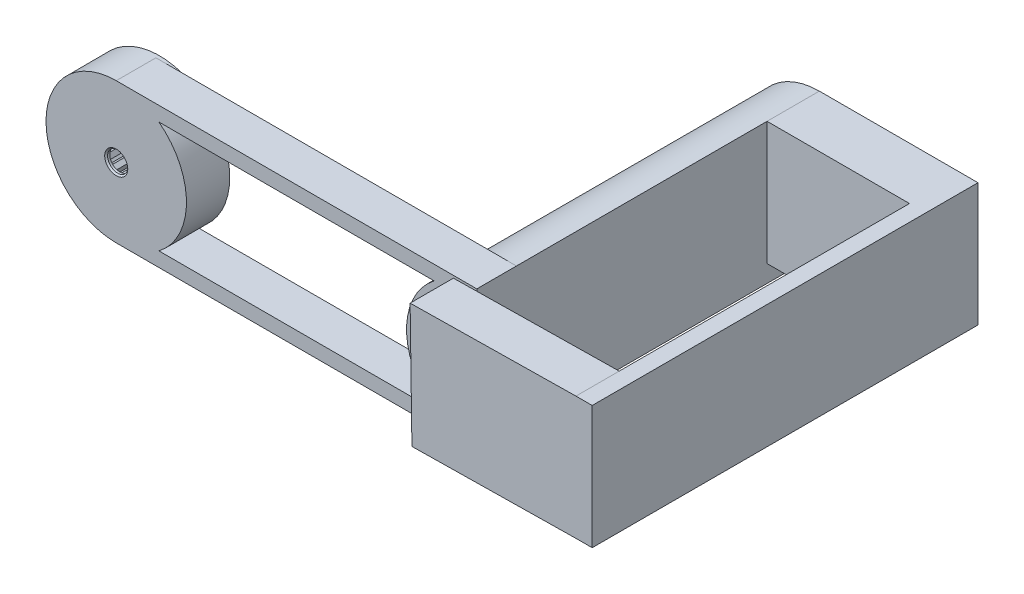
SolidWorks part; units mm, degrees
ref_plane "Plan de face" through (0, 0, 0) normal (0, 0, 1) x (1, 0, 0)
ref_plane "Plan de dessus" through (0, 0, 0) normal (0, 1, 0) x (1, 0, 0)
ref_plane "Plan de droite" through (0, 0, 0) normal (1, 0, 0) x (0, 0, -1)
sketch "Esquisse1" plane through (0, 0, 0) normal (0, 0, 1) x (1, 0, 0)
  line L108 (-5.7517, -9.8772) -> (-6.8338, -9.7825)
  line L109 (-6.8338, -9.7825) -> (-6.9494, -9.1264)
  line L110 (-6.9494, -9.1264) -> (-5.9535, -8.662)
  line L111 (-6.0657, -8.3442) -> (-7.1383, -8.6316)
  line L112 (-7.1383, -8.6316) -> (-7.4714, -8.0546)
  line L113 (-7.4714, -8.0546) -> (-6.6788, -7.262)
  line L114 (-6.8912, -7.0053) -> (-7.818, -7.6542)
  line L115 (-7.818, -7.6542) -> (-8.3284, -7.226)
  line L116 (-8.3284, -7.226) -> (-7.8476, -6.1949)
  line L117 (-8.1333, -6.0289) -> (-8.7911, -6.9683)
  line L118 (-8.7911, -6.9683) -> (-9.4172, -6.7405)
  line L119 (-9.4172, -6.7405) -> (-9.3172, -5.5977)
  line L120 (-9.6413, -5.5414) -> (-9.9401, -6.6566)
  line L121 (-9.9401, -6.6566) -> (-10.6064, -6.6566)
  line L122 (-10.6064, -6.6566) -> (-10.9035, -5.5477)
  line L123 (-11.227, -5.6073) -> (-11.1264, -6.7566)
  line L124 (-11.1264, -6.7566) -> (-11.7525, -6.9845)
  line L125 (-11.7525, -6.9845) -> (-12.4065, -6.0504)
  line L126 (-12.6906, -6.2193) -> (-12.207, -7.2564)
  line L127 (-12.207, -7.2564) -> (-12.7173, -7.6846)
  line L128 (-12.7173, -7.6846) -> (-13.6389, -7.0393)
  line L129 (-13.8487, -7.2983) -> (-13.0514, -8.0955)
  line L130 (-13.0514, -8.0955) -> (-13.3846, -8.6725)
  line L131 (-13.3846, -8.6725) -> (-14.4509, -8.3868)
  line L132 (-14.5599, -8.7057) -> (-13.558, -9.1729)
  line L133 (-13.558, -9.1729) -> (-13.6737, -9.8291)
  line L134 (-13.6737, -9.8291) -> (-14.7493, -9.9232)
  line L135 (-14.7422, -10.2644) -> (-13.6655, -10.3586)
  line L136 (-13.6655, -10.3586) -> (-13.5498, -11.0147)
  line L137 (-13.5498, -11.0147) -> (-14.5063, -11.4608)
  line L138 (-14.3817, -11.783) -> (-13.3609, -11.5095)
  line L139 (-13.3609, -11.5095) -> (-13.0278, -12.0865)
  line L140 (-13.0278, -12.0865) -> (-13.7588, -12.8175)
  line L141 (-13.5298, -13.0811) -> (-12.6812, -12.4869)
  line L142 (-12.6812, -12.4869) -> (-12.1708, -12.9151)
  line L143 (-12.1708, -12.9151) -> (-12.6007, -13.8372)
  line L144 (-12.2937, -14.0091) -> (-11.7081, -13.1728)
  line L145 (-11.7081, -13.1728) -> (-11.082, -13.4007)
  line L146 (-11.082, -13.4007) -> (-11.1699, -14.405)
  line L147 (-10.8214, -14.4636) -> (-10.5591, -13.4845)
  line L148 (-10.5591, -13.4845) -> (-9.8929, -13.4845)
  line L149 (-9.8929, -13.4845) -> (-9.6322, -14.4574)
  line L150 (-9.2844, -14.3952) -> (-9.3728, -13.3845)
  line L151 (-9.3728, -13.3845) -> (-8.7467, -13.1566)
  line L152 (-8.7467, -13.1566) -> (-8.1648, -13.9877)
  line L153 (-7.8596, -13.8126) -> (-8.2922, -12.8848)
  line L154 (-8.2922, -12.8848) -> (-7.7819, -12.4565)
  line L155 (-7.7819, -12.4565) -> (-6.9385, -13.047)
  line L156 (-6.7123, -12.7811) -> (-7.4478, -12.0456)
  line L157 (-7.4478, -12.0456) -> (-7.1146, -11.4686)
  line L158 (-7.1146, -11.4686) -> (-6.1002, -11.7404)
  line L159 (-5.9789, -11.4169) -> (-6.9412, -10.9682)
  line L160 (-6.9412, -10.9682) -> (-6.8255, -10.3121)
  line L161 (-6.8255, -10.3121) -> (-5.7553, -10.2184)
  arc A1 (-5.073, -1.75) -> (-5.073, -18.25) centre (-10.25, -10) ccw
  circle A2 centre (-10.25, -10) radius 9.7398
  arc A36 (-5.9535, -8.662) -> (-6.0657, -8.3442) centre (-10.25, -10) ccw
  arc A37 (-6.6788, -7.262) -> (-6.8912, -7.0053) centre (-10.25, -10) ccw
  arc A38 (-7.8476, -6.1949) -> (-8.1333, -6.0289) centre (-10.25, -10) ccw
  arc A39 (-9.3172, -5.5977) -> (-9.6413, -5.5414) centre (-10.25, -10) ccw
  arc A40 (-10.9035, -5.5477) -> (-11.227, -5.6073) centre (-10.25, -10) ccw
  arc A41 (-12.4065, -6.0504) -> (-12.6906, -6.2193) centre (-10.25, -10) ccw
  arc A42 (-13.6389, -7.0393) -> (-13.8487, -7.2983) centre (-10.25, -10) ccw
  arc A43 (-14.4509, -8.3868) -> (-14.5599, -8.7057) centre (-10.25, -10) ccw
  arc A44 (-14.7493, -9.9232) -> (-14.7422, -10.2644) centre (-10.25, -10) ccw
  arc A45 (-14.5063, -11.4608) -> (-14.3817, -11.783) centre (-10.25, -10) ccw
  arc A46 (-13.7588, -12.8175) -> (-13.5298, -13.0811) centre (-10.25, -10) ccw
  arc A47 (-12.6007, -13.8372) -> (-12.2937, -14.0091) centre (-10.25, -10) ccw
  arc A48 (-11.1699, -14.405) -> (-10.8214, -14.4636) centre (-10.25, -10) ccw
  arc A49 (-9.6322, -14.4574) -> (-9.2844, -14.3952) centre (-10.25, -10) ccw
  arc A50 (-8.1648, -13.9877) -> (-7.8596, -13.8126) centre (-10.25, -10) ccw
  arc A51 (-6.9385, -13.047) -> (-6.7123, -12.7811) centre (-10.25, -10) ccw
  arc A52 (-6.1002, -11.7404) -> (-5.9789, -11.4169) centre (-10.25, -10) ccw
  arc A53 (-5.7553, -10.2184) -> (-5.7517, -9.8772) centre (-10.25, -10) ccw
extrude "Boss.-Extru.1" add sketch "Esquisse1" along normal blind 5.5 contours A1 A2 A53 L161 L160 L159 A52 L158 L157 L156 A51 L155 L154 L153 A50 L152 L151 L150 A49 L149 L148 L147 A48 L146 L145 L144 A47 L143 L142 L141 A46 L140 L139 L138 A45 L137 L136 L135 A44 L134 L133 L132 A43 L131 L130 L129 A42 L128 L127 L126
sketch "Esquisse2" plane through (0, 0, 5.5) normal (0, 0, 1) x (1, 0, 0)
  circle A0 centre (-10.2496, -10.0706) radius 1.4 construction
  circle A1 centre (-10.25, -10) radius 9.7398
  circle A2 centre (-10.25, -10) radius 9.7398
  circle A3 centre (-10.2496, -10.0706) radius 1.4
  dimension "D1" = 0
extrude "Boss.-Extru.2" add sketch "Esquisse2" along normal blind 0.5
chamfer "Chanfrein1" distance 0.2 angle 45 1 edges at (-8.8496, -10.0706, 6)
sketch "Esquisse3" plane through (0, 0, 6) normal (0, 0, 1) x (1, 0, 0)
  line L0 (-10.25, -0.2602) -> (39.75, -0.2602)
  line L3 (39.75, -0.2602) -> (39.75, -19.7398)
  line L4 (39.75, -19.7398) -> (-10.25, -19.7398)
  line L5 (33.8374, -17.7398) -> (-10.25, -17.7398)
  line L6 (-10.25, -2.2602) -> (33.8374, -2.2602)
  line L9 (-10.25, -2.2602) -> (37.75, -2.2602) construction
  line L10 (37.75, -2.2602) -> (37.75, -17.7398) construction
  line L11 (37.75, -17.7398) -> (-10.25, -17.7398) construction
  arc A1 (-10.25, -2.2602) -> (-10.25, -17.7398) centre (-10.25, -10) ccw
  circle A2 centre (-10.25, -10) radius 9.7398
  arc A3 (-10.25, -0.2602) -> (-10.25, -19.7398) centre (-10.25, -10) ccw
  arc A4 (33.8374, -2.2602) -> (33.8374, -17.7398) centre (39.75, -10) ccw
  point P6 (-10.25, -10.0706)
  dimension "D1" = 0
  dimension "D2" = 50
  dimension "D3" = 2
extrude "Boss.-Extru.3" add sketch "Esquisse3" against normal blind 5.5
sketch "Esquisse4" plane through (0, 0, 0.5) normal (0, 0, -1) x (-1, 0, 0)
  line L0 (-39.75, -19.7398) -> (-39.75, -0.2602) construction
  line L1 (-39.75, -0.2602) -> (-39.75, -19.7398)
  arc A0 (-39.75, -19.7398) -> (-39.75, -0.2602) centre (-39.75, -10) ccw
extrude "Boss.-Extru.4" add sketch "Esquisse4" along normal blind 42
sketch "Esquisse5" plane through (39.75, 0, 0) normal (1, 0, 0) x (0, 0, -1)
  line L0 (34.25, -17.3476) -> (41.5, -17.3476)
  line L1 (41.5, -0.2602) -> (34.25, -0.2602)
  line L2 (41.5, -0.2602) -> (41.5, -17.3476)
  line L3 (41.5, -0.2602) -> (41.5, -19.7398) construction
  line L6 (-6, -0.2602) -> (-6, -19.7398)
  line L7 (-6, -19.7398) -> (-0.5, -19.7398)
  line L8 (-0.5, -19.7398) -> (41.5, -19.7398)
  line L9 (41.5, -19.7398) -> (41.5, -0.2602)
  line L10 (41.5, -0.2602) -> (-0.5, -0.2602)
  line L11 (-0.5, -0.2602) -> (-6, -0.2602)
  line L16 (41.5, -0.2602) -> (34.25, -0.2602)
  line L24 (39.5, -17.3476) -> (34.25, -17.3476)
  line L25 (34.25, -17.3476) -> (34.25, 10.6524)
  line L26 (34.25, 10.6524) -> (-5.75, 10.6524)
  line L27 (-5.75, 10.6524) -> (-5.75, -17.3476)
  line L28 (-5.75, -17.3476) -> (-11, -17.3476)
  line L29 (-11, -17.3476) -> (-11, -19.3476)
  line L30 (-11, -19.3476) -> (-5.75, -19.3476)
  line L31 (-5.75, -19.3476) -> (-5.75, -28.8476)
  line L32 (-5.75, -28.8476) -> (34.25, -28.8476)
  line L33 (34.25, -28.8476) -> (34.25, -19.3476)
  line L34 (34.25, -19.3476) -> (39.5, -19.3476)
  line L35 (39.5, -19.3476) -> (39.5, -17.3476)
  line L37 (34.25, -17.3476) -> (34.25, -0.2602)
  line M22 (41.5, -19.7398) -> (41.5, -0.2602)
  line M23 (41.5, -0.2602) -> (-0.5, -0.2602)
  dimension "D1" = 0
  dimension "D2" = 0
extrude "Boss.-Extru.5" add sketch "Esquisse5" along normal blind 22 contours L37 L0 M22 M23
sketch "Esquisse6" plane through (0, 0, -34.25) normal (0, 0, 1) x (1, 0, 0)
  line L0 (-59.5, 0.2602) -> (59.5, -0.2602)
  line L1 (59.5, -17.3476) -> (59.5, 10.6524) construction
  line L2 (59.5, -0.2602) -> (59.75, -17.3476)
  line L3 (59.75, -17.3476) -> (59.75, 10.6524) construction
  line L4 (39.75, -0.2602) -> (39.75, -17.3476)
  line L5 (39.75, -17.3476) -> (61.75, -17.3476)
  line L6 (61.75, -17.3476) -> (61.75, -0.2602)
  line L7 (61.75, -0.2602) -> (39.75, -0.2602)
  line L8 (39.75, -0.2602) -> (39.75, -17.3476)
  line L9 (39.75, -17.3476) -> (61.75, -17.3476)
  line L10 (61.75, -17.3476) -> (61.75, -0.2602)
  line L11 (61.75, -0.2602) -> (39.75, -0.2602)
  point P10 (0, 0)
  line M6 (39.75, -17.3476) -> (61.75, -17.3476)
  line M7 (61.75, -17.3476) -> (61.75, -0.2602)
  line M8 (61.75, -0.2602) -> (39.75, -0.2602)
  dimension "D1" = 0
extrude "Boss.-Extru.6" add sketch "Esquisse6" along normal blind 46.25 contours L2 M8 M6 M7
sketch "Esquisse7" plane through (59.4835, 0.8703, 0) normal (-0.9999, -0.0146, 0) x (0, 0, 1)
  line L0 (6, -20.3192) -> (6, -0.8417) construction
  line L1 (6, -18.2198) -> (6, -1.1306)
  line L4 (-34.25, -1.1306) -> (-34.25, -18.2198)
  line L5 (-34.25, -18.2198) -> (12, -18.2198)
  line L6 (12, -18.2198) -> (12, -1.1306)
  line L7 (12, -1.1306) -> (-34.25, -1.1306)
  line L9 (6, -18.2198) -> (12, -18.2198)
  line L10 (12, -18.2198) -> (12, -1.1306)
  line L11 (12, -1.1306) -> (6, -1.1306)
  dimension "D1" = 0
extrude "Boss.-Extru.7" add sketch "Esquisse7" along normal blind 23
